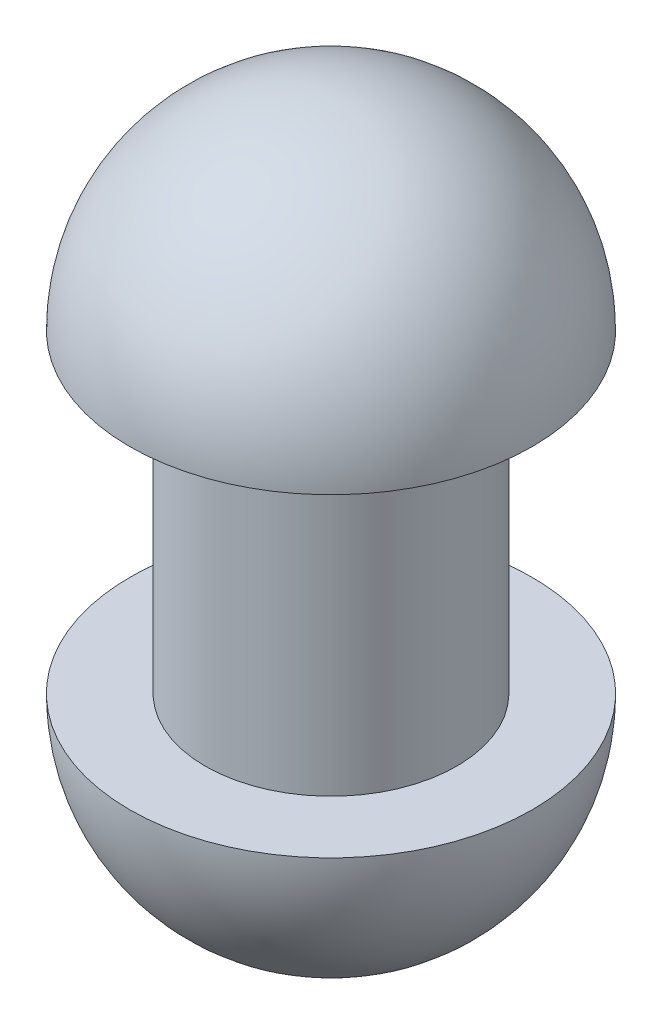
SolidWorks part; units mm, degrees
ref_plane "Front Plane" through (0, 0, 0) normal (0, 0, 1) x (1, 0, 0)
ref_plane "Top Plane" through (0, 0, 0) normal (0, 1, 0) x (1, 0, 0)
ref_plane "Right Plane" through (0, 0, 0) normal (1, 0, 0) x (0, 0, -1)
sketch "Sketch1" plane through (0, 0, 0) normal (0, 0, 1) x (1, 0, 0)
  line L0 (0, 0) -> (0, -43.0911) construction
  line L1 (9, -6.1911) -> (9, -28.6911)
  line L2 (9, -6.1911) -> (14.4, -6.1911)
  line L3 (9, -28.6911) -> (14.4, -28.6911)
  line L4 (0, 8.2089) -> (0, -43.0911)
  arc A0 (14.4, -6.1911) -> (0, 8.2089) centre (0, -6.1911) ccw
  arc A1 (14.4, -28.6911) -> (0, -43.0911) centre (0, -28.6911) cw
  point P11 (10.1823, -38.8734)
  point P12 (10.1823, 3.9912)
  point P13 (0, 0)
  point P14 (0, 0)
  point P15 (0, 0)
  dimension "D1" = 14.4
  dimension "D2" = 14.4
  dimension "D3" = 9
  dimension "D4" = 22.5
revolve "Revolve1" add sketch "Sketch1" angle 360 about L0
